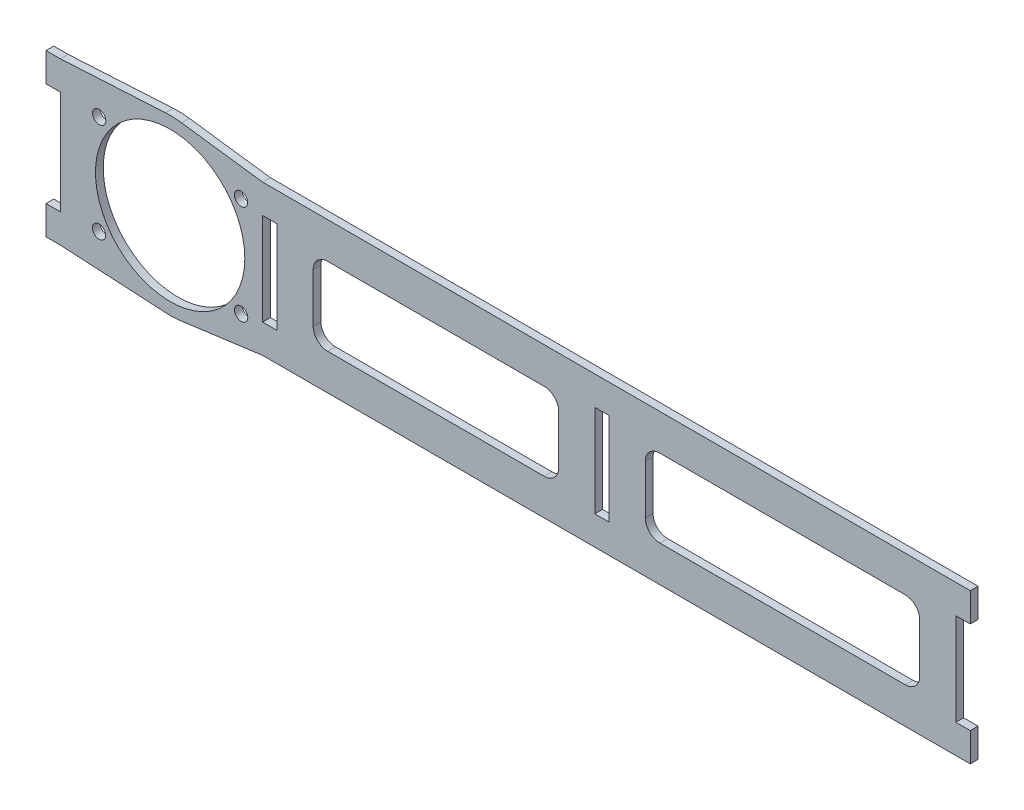
SolidWorks part; units mm, degrees
ref_plane "Front Plane" through (0, 0, 0) normal (0, 0, 1) x (1, 0, 0)
ref_plane "Top Plane" through (0, 0, 0) normal (0, 1, 0) x (1, 0, 0)
ref_plane "Right Plane" through (0, 0, 0) normal (1, 0, 0) x (0, 0, -1)
sketch "Sketch1" plane through (0, 0, 0) normal (0, 0, 1) x (1, 0, 0)
  line L0 (6399.6201, 3384.1874) -> (6399.6201, 3343.5982)
  line L1 (6310.7201, 3386.6766) -> (6310.7201, 3341.109)
  line L2 (6405.9701, 3343.5982) -> (6399.6201, 3343.5982)
  line L3 (6405.9701, 3343.5982) -> (6405.9701, 3384.1874)
  line L4 (6421.8451, 3353.1232) -> (6421.8451, 3374.6624)
  line L5 (6405.9701, 3384.1874) -> (6399.6201, 3384.1874)
  line L6 (6304.3701, 3341.109) -> (6304.3701, 3328.409)
  line L7 (6304.3701, 3386.6766) -> (6304.3701, 3399.3766)
  line L8 (6304.3701, 3341.109) -> (6310.7201, 3341.109)
  line L9 (6304.3701, 3386.6766) -> (6310.7201, 3386.6766)
  line L10 (6710.7701, 3396.8874) -> (6399.6201, 3396.8874)
  line L11 (6682.1951, 3381.0124) -> (6574.2451, 3381.0124)
  line L12 (6523.4451, 3381.0124) -> (6428.1951, 3381.0124)
  line L13 (6710.7701, 3330.8982) -> (6399.6201, 3330.8982)
  line L14 (6682.1951, 3346.7732) -> (6574.2451, 3346.7732)
  line L15 (6523.4451, 3346.7732) -> (6428.1951, 3346.7732)
  line L16 (6545.6701, 3384.1874) -> (6545.6701, 3343.5982)
  line L17 (6529.7951, 3374.6624) -> (6529.7951, 3353.1232)
  line L18 (6552.0201, 3343.5982) -> (6545.6701, 3343.5982)
  line L19 (6552.0201, 3343.5982) -> (6552.0201, 3384.1874)
  line L20 (6567.8951, 3353.1232) -> (6567.8951, 3374.6624)
  line L21 (6704.4201, 3343.5982) -> (6704.4201, 3384.1874)
  line L22 (6688.5451, 3353.1232) -> (6688.5451, 3374.6624)
  line L23 (6710.7701, 3343.5982) -> (6710.7701, 3330.8982)
  line L24 (6552.0201, 3384.1874) -> (6545.6701, 3384.1874)
  line L25 (6710.7701, 3343.5982) -> (6704.4201, 3343.5982)
  line L26 (6710.7701, 3396.8874) -> (6710.7701, 3384.1874)
  line L27 (6710.7701, 3384.1874) -> (6704.4201, 3384.1874)
  line L28 (6304.3701, 3399.3766) -> (6310.7201, 3399.3766)
  line L29 (6304.3701, 3328.409) -> (6310.7201, 3328.409)
  line L30 (6310.7201, 3399.3766) -> (6356.8499, 3401.9344)
  line L31 (6399.6201, 3396.8874) -> (6364.0166, 3401.6556)
  line L32 (6310.7201, 3328.409) -> (6356.8499, 3325.8512)
  line L33 (6399.6201, 3330.8982) -> (6364.0166, 3326.1299)
  arc A0 (6421.8451, 3353.1232) -> (6428.1951, 3346.7732) centre (6428.1951, 3353.1232) ccw
  arc A1 (6428.1951, 3381.0124) -> (6421.8451, 3374.6624) centre (6428.1951, 3374.6624) ccw
  arc A2 (6688.5451, 3374.6624) -> (6682.1951, 3381.0124) centre (6682.1951, 3374.6624) ccw
  arc A3 (6529.7951, 3374.6624) -> (6523.4451, 3381.0124) centre (6523.4451, 3374.6624) ccw
  arc A4 (6523.4451, 3346.7732) -> (6529.7951, 3353.1232) centre (6523.4451, 3353.1232) ccw
  arc A5 (6567.8951, 3353.1232) -> (6574.2451, 3346.7732) centre (6574.2451, 3353.1232) ccw
  arc A6 (6574.2451, 3381.0124) -> (6567.8951, 3374.6624) centre (6574.2451, 3374.6624) ccw
  arc A7 (6682.1951, 3346.7732) -> (6688.5451, 3353.1232) centre (6682.1951, 3353.1232) ccw
  circle A8 centre (6358.9592, 3363.8928) radius 32.8295
  circle A9 centre (6327.7088, 3342.0978) radius 2.921
  circle A10 centre (6390.1689, 3342.0395) radius 2.921
  circle A11 centre (6390.1273, 3385.8054) radius 2.921
  circle A12 centre (6327.7495, 3385.746) radius 2.921
  arc A13 (6364.0166, 3401.6556) -> (6356.8499, 3401.9344) centre (6358.9592, 3363.8928) ccw
  arc A14 (6356.8499, 3325.8512) -> (6364.0166, 3326.1299) centre (6358.9592, 3363.8928) ccw
extrude "Boss-Extrude1" add sketch "Sketch1" along normal blind 3.4036
